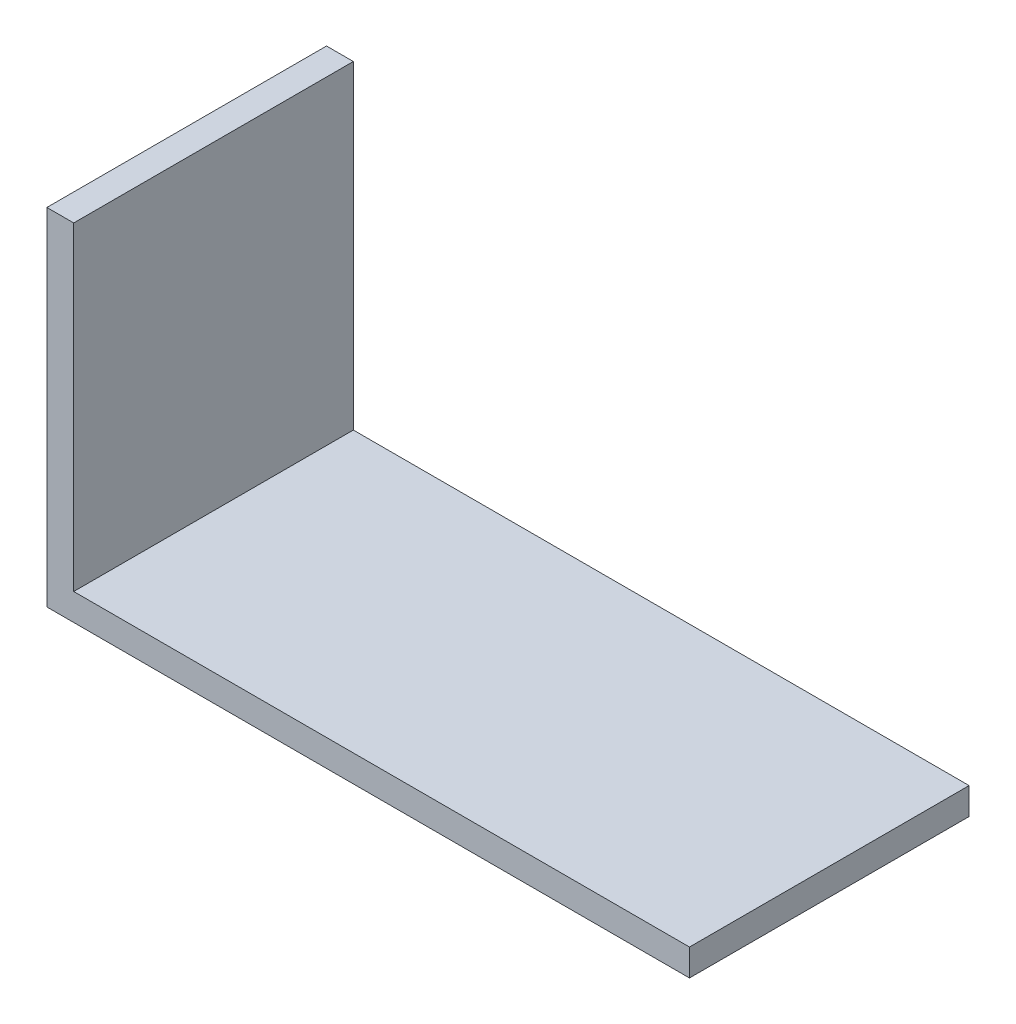
SolidWorks part; units mm, degrees
ref_plane "Plan de face" through (0, 0, 0) normal (0, 0, 1) x (1, 0, 0)
ref_plane "Plan de dessus" through (0, 0, 0) normal (0, 1, 0) x (1, 0, 0)
ref_plane "Plan de droite" through (0, 0, 0) normal (1, 0, 0) x (0, 0, -1)
sketch "Esquisse1" plane through (0, 0, 0) normal (0, 0, 1) x (1, 0, 0)
  line L0 (0, 0) -> (455, 0)
  line L1 (0, 0) -> (0, 245)
  dimension "D1" = 455
  dimension "D2" = 245
extrude "Extru.-Mince1" add sketch "Esquisse1" along normal blind 198 thin thin type one direction wall 19
